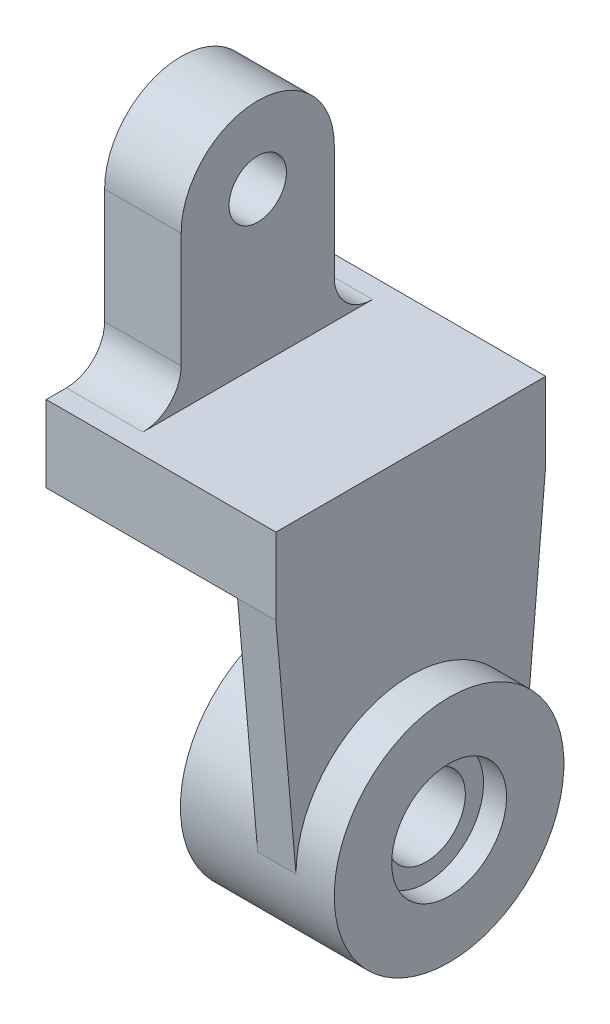
SolidWorks part; units mm, degrees
ref_plane "Front Plane" through (0, 0, 0) normal (0, 0, 1) x (1, 0, 0)
ref_plane "Top Plane" through (0, 0, 0) normal (0, 1, 0) x (1, 0, 0)
ref_plane "Right Plane" through (0, 0, 0) normal (1, 0, 0) x (0, 0, -1)
sketch "Sketch1" plane through (0, 0, 0) normal (0, 0, 1) x (1, 0, 0)
  line L5 (-30, 10) -> (30, 10)
  line L6 (-30, 10) -> (-30, -10)
  line L7 (-30, -10) -> (20, -10)
  line L8 (30, 10) -> (30, -70)
  line L11 (20, -70) -> (30, -70)
  line L12 (20, -70) -> (20, -10)
  point P0 (0, 0)
  point P1 (0, 0)
  point P2 (0, 0)
  point P7 (0, 0)
  dimension "D1" = 60
  dimension "D2" = 30
  dimension "D3" = 60
  dimension "D4" = 20
  dimension "D5" = 10
  dimension "D6" = 20
extrude "Boss-Extrude1" add sketch "Sketch1" against normal blind 70.5
sketch "Sketch2" plane through (30, 0, 0) normal (1, 0, 0) x (0, 0, -1)
  line L0 (70.5, -70) -> (0, -70) construction
  line L1 (0, 10) -> (70.5, 10)
  line L2 (0, -10) -> (70.5, -10)
  circle A0 centre (35.25, -70) radius 30
  circle A1 centre (35.25, -70) radius 15
  circle A2 centre (35.25, -70) radius 10.25
  dimension "D1" = 60
  dimension "D2" = 30
  dimension "D3" = 20.5
  dimension "D4" = 20
extrude "Boss-Extrude2" add sketch "Sketch2" along normal blind 10 and the other way blind 30.2 contours A0
sketch "Sketch3" plane through (40, 0, 0) normal (1, 0, 0) x (0, 0, -1)
  circle A0 centre (35.25, -70) radius 15
  circle A1 centre (35.25, -70) radius 10.25
  dimension "D1" = 30
  dimension "D2" = 20.5
extrude "Cut-Extrude1" cut sketch "Sketch3" against normal blind 92 contours A1
sketch "Sketch4" plane through (40, 0, 0) normal (1, 0, 0) x (0, 0, -1)
  circle A0 centre (35.25, -70) radius 15
  dimension "D1" = 30
extrude "Cut-Extrude2" cut sketch "Sketch4" against normal blind 6
sketch "Sketch5" plane through (30, 0, 0) normal (1, 0, 0) x (0, 0, -1)
  line L2 (0, -10) -> (5.25, -70)
  line L3 (65.25, -70) -> (70.5, -10)
  point P0 (0, 0)
  dimension "D1" = 60
  dimension "D2" = 10
  dimension "D3" = 10
extrude "Cut-Extrude-Thin1" cut sketch "Sketch5" against normal blind 53 thin contours L2 | L3
sketch "Sketch7" plane through (-30, 0, 0) normal (-1, 0, 0) x (0, 0, 1)
  line L0 (0, 10) -> (0, -10) construction
  line L2 (-55.25, 50) -> (-55.25, 20)
  line L3 (-70.5, 10) -> (0, 10) construction
  line L4 (-15.25, 50) -> (-15.25, 20)
  line L5 (-70.5, 10) -> (-65.25, 10)
  line L6 (-5.25, 10) -> (0, 10)
  arc A0 (-15.25, 50) -> (-55.25, 50) centre (-35.25, 50) ccw
  circle A1 centre (-35.25, 50) radius 7.5
  arc A2 (-55.25, 20) -> (-65.25, 10) centre (-65.25, 20) cw
  arc A3 (-5.25, 10) -> (-15.25, 20) centre (-5.25, 20) cw
  point P17 (-55.25, 10)
  point P20 (-15.25, 10)
  line M3 (0, 10) -> (-70.5, 10)
  dimension "D2" = 40
  dimension "D3" = 15
  dimension "D4" = 10
  dimension "D5" = 10
  dimension "D1" = 35.25
  dimension "D6" = 40
extrude "Boss-Extrude5" add sketch "Sketch7" against normal blind 20 contours A3 L4 A0 L2 A2 A1 M3
